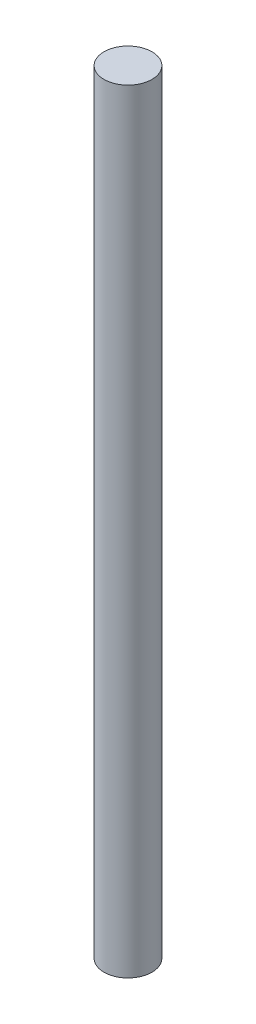
SolidWorks part; units mm, degrees
ref_plane "Front" through (0, 0, 0) normal (0, 0, 1) x (1, 0, 0)
ref_plane "Top" through (0, 0, 0) normal (0, 1, 0) x (1, 0, 0)
ref_plane "Right" through (0, 0, 0) normal (1, 0, 0) x (0, 0, -1)
sketch "Sketch1" plane through (0, 0, 0) normal (0, 1, 0) x (1, 0, 0)
  circle A0 centre (0, 0) radius 1.55
  dimension "D1" = 3.1
extrude "Boss-Extrude1" add sketch "Sketch1" along normal blind 50
